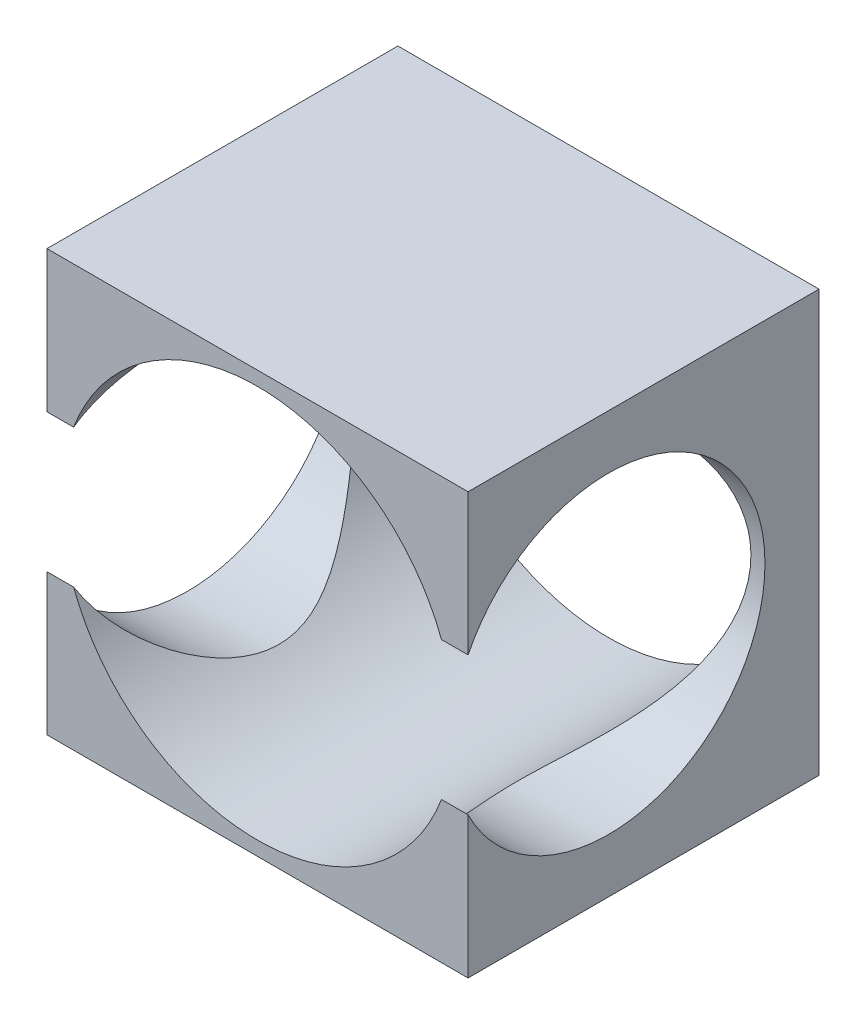
SolidWorks part; units mm, degrees
ref_plane "前视基准面" through (0, 0, 0) normal (0, 0, 1) x (1, 0, 0)
ref_plane "上视基准面" through (0, 0, 0) normal (0, 1, 0) x (1, 0, 0)
ref_plane "右视基准面" through (0, 0, 0) normal (1, 0, 0) x (0, 0, -1)
sketch "草图1" plane through (0, 0, 0) normal (0, 0, 1) x (1, 0, 0)
  line L1 (15, 15) -> (-15, 15)
  line L2 (15, 15) -> (15, -15)
  line L3 (15, -15) -> (-15, -15)
  line L4 (-15, 15) -> (-15, -15)
  line L5 (15, 15) -> (-15, -15) construction
  line L6 (15, -15) -> (-15, 15) construction
  circle A0 centre (0, 0) radius 14
  point P0 (0, 0)
  dimension "D1" = 30
  dimension "D2" = 30
extrude "凸台-拉伸1" add sketch "草图1" along normal blind 25
sketch "草图2" plane through (-15, 0, 0) normal (-1, 0, 0) x (0, 0, 1)
  line L0 (25, 15) -> (25, -15) construction
  circle A0 centre (15, 0) radius 11.15
  dimension "D1" = 10
extrude "切除-拉伸1" cut sketch "草图2" against normal through all
sketch "草图3" plane through (0, 0, 0) normal (0, 0, -1) x (-1, 0, 0)
  line L0 (15, 15) -> (15, -15) construction
  line L1 (-15, 15) -> (15, 15) construction
  circle A0 centre (12, 12) radius 1.3634
  circle A1 centre (12, -12) radius 1.3634
  circle A2 centre (-12, -12) radius 1.3634
  circle A3 centre (-12, 12) radius 1.3634
  point P15 (0, 0)
  dimension "D1" = 3
  dimension "D2" = 3
  dimension "D3" = 4
extrude "切除-拉伸2" cut sketch "草图3" against normal blind 5
